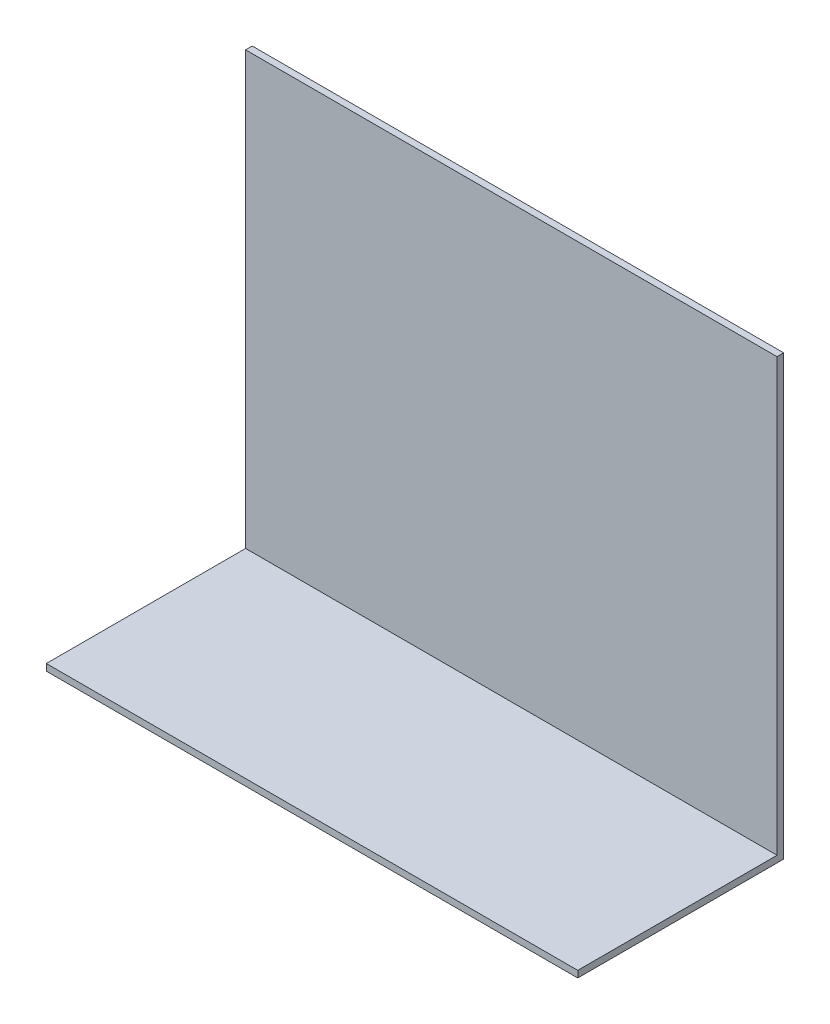
SolidWorks part; units mm, degrees
material "Acrylic (Medium-high impact)"
ref_plane "Front Plane" through (0, 0, 0) normal (0, 0, 1) x (1, 0, 0)
ref_plane "Top Plane" through (0, 0, 0) normal (0, 1, 0) x (1, 0, 0)
ref_plane "Right Plane" through (0, 0, 0) normal (1, 0, 0) x (0, 0, -1)
sketch "Sketch1" plane through (0, 0, 0) normal (0, 0, 1) x (1, 0, 0)
  line L1 (-200, -165) -> (200, -165)
  line L2 (-200, -165) -> (-200, 165)
  line L3 (-200, 165) -> (200, 165)
  line L4 (200, -165) -> (200, 165)
  line L5 (-200, -165) -> (200, 165) construction
  line L6 (-200, 165) -> (200, -165) construction
  point P0 (0, 0)
extrude "Boss-Extrude1" add sketch "Sketch1" along normal blind 5
sketch "Sketch2" plane through (0, 0, 0) normal (0, 0, 1) x (1, 0, 0)
  line L0 (200, -165) -> (200, 165) construction
  line L1 (-200, -165) -> (200, -165)
  line L2 (-200, -165) -> (-200, -160)
  line L3 (-200, -160) -> (200, -160)
  line L4 (200, -165) -> (200, -160)
extrude "Boss-Extrude2" add sketch "Sketch2" along normal blind 150 from surface at 5 starting at face at (0, 0, 5)
